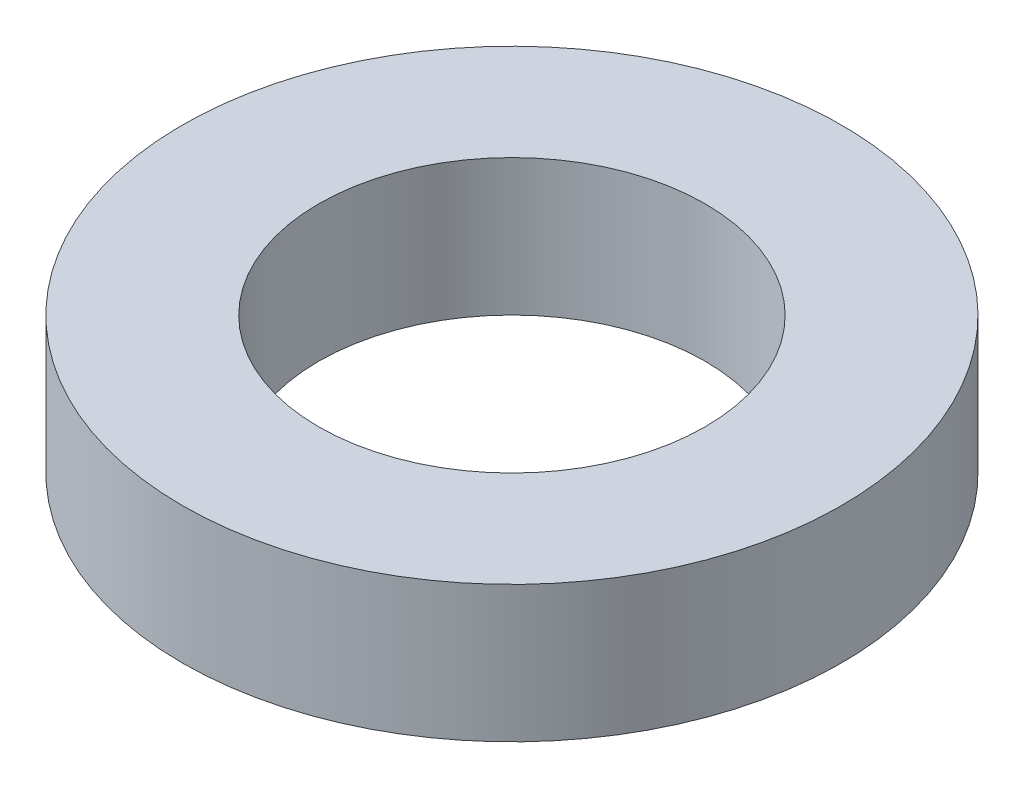
SolidWorks part; units mm, degrees
ref_plane "Front Plane" through (0, 0, 0) normal (0, 0, 1) x (1, 0, 0)
ref_plane "Top Plane" through (0, 0, 0) normal (0, 1, 0) x (1, 0, 0)
ref_plane "Right Plane" through (0, 0, 0) normal (1, 0, 0) x (0, 0, -1)
sketch "Sketch1" plane through (0, 0, 0) normal (0, 1, 0) x (1, 0, 0)
  circle A0 centre (0, 0) radius 7.25
  circle A1 centre (0, 0) radius 4.25
  dimension "D1" = 8.5
  dimension "D2" = 14.5
extrude "Boss-Extrude1" add sketch "Sketch1" along normal blind 3
